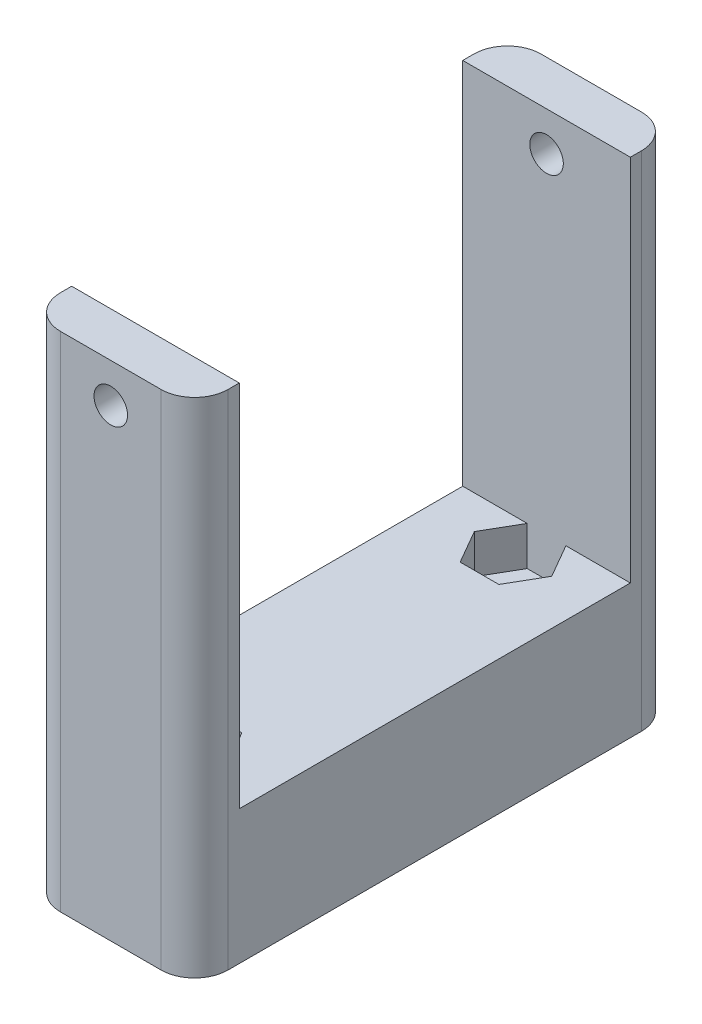
SolidWorks part; units mm, degrees
ref_plane "Alzado" through (0, 0, 0) normal (0, 0, 1) x (1, 0, 0)
ref_plane "Planta" through (0, 0, 0) normal (0, 1, 0) x (1, 0, 0)
ref_plane "Vista lateral" through (0, 0, 0) normal (1, 0, 0) x (0, 0, -1)
sketch "Croquis1" plane through (0, 0, 0) normal (0, 1, 0) x (1, 0, 0)
  line L1 (-7.5, 21.5) -> (7.5, 21.5)
  line L2 (-7.5, 21.5) -> (-7.5, -21.5)
  line L3 (-7.5, -21.5) -> (7.5, -21.5)
  line L4 (7.5, 21.5) -> (7.5, -21.5)
  point P4 (7.5, 0)
  point P6 (0, -21.5)
  dimension "D1" = 43
  dimension "D2" = 15
extrude "Saliente-Extruir1" add sketch "Croquis1" along normal blind 12
sketch "Croquis2" plane through (0, 12, 0) normal (0, 1, 0) x (1, 0, 0)
  line L0 (7.5, -21.5) -> (7.5, 21.5) construction
  line L1 (-7.5, 21.5) -> (7.5, 21.5)
  line L2 (-7.5, 21.5) -> (-7.5, 17.5)
  line L3 (-7.5, 17.5) -> (7.5, 17.5)
  line L4 (7.5, 21.5) -> (7.5, 17.5)
  line L5 (-7.5, 21.5) -> (-7.5, -21.5) construction
  line L6 (7.5, -21.5) -> (-7.5, -21.5)
  line L7 (7.5, -21.5) -> (7.5, -17.5)
  line L8 (7.5, -17.5) -> (-7.5, -17.5)
  line L9 (-7.5, -21.5) -> (-7.5, -17.5)
  dimension "D1" = 4
  dimension "D2" = 4
extrude "Saliente-Extruir2" add sketch "Croquis2" along normal blind 33
sketch "Croquis3" plane through (0, 0, 0) normal (0, -1, 0) x (1, 0, 0)
  line L0 (0, 14.5) -> (0, -14.5) construction
  circle A0 centre (0, 14.5) radius 1.5
  circle A1 centre (0, -14.5) radius 1.5
  point P4 (0, 0)
  dimension "D1" = 3
  dimension "D2" = 3
  dimension "D3" = 26
extrude "Cortar-Extruir1" cut sketch "Croquis3" against normal blind 13
sketch "Croquis4" plane through (0, 12, 0) normal (0, 1, 0) x (1, 0, 0)
  line L1 (3.4641, 14.5) -> (1.7321, 17.5)
  line L2 (1.7321, 17.5) -> (-1.7321, 17.5)
  line L3 (-1.7321, 17.5) -> (-3.4641, 14.5)
  line L4 (-3.4641, 14.5) -> (-1.7321, 11.5)
  line L5 (-1.7321, 11.5) -> (1.7321, 11.5)
  line L6 (1.7321, 11.5) -> (3.4641, 14.5)
  line L7 (3.4641, -14.5) -> (1.7321, -11.5)
  line L8 (1.7321, -11.5) -> (-1.7321, -11.5)
  line L9 (-1.7321, -11.5) -> (-3.4641, -14.5)
  line L10 (-3.4641, -14.5) -> (-1.7321, -17.5)
  line L11 (-1.7321, -17.5) -> (1.7321, -17.5)
  line L12 (1.7321, -17.5) -> (3.4641, -14.5)
  circle A0 centre (0, 14.5) radius 3 construction
  circle A1 centre (0, -14.5) radius 3 construction
  circle A2 centre (0, -14.5) radius 1.5 construction
  point P10 (0, 0)
  dimension "D1" = 6
  dimension "D2" = 6
extrude "Cortar-Extruir2" cut sketch "Croquis4" against normal blind 3.5
fillet "Redondeo1" radius 3 4 edges at (7.5, 22.5, 21.5) (-7.5, 22.5, 21.5) (7.5, 22.5, -21.5) (-7.5, 22.5, -21.5)
sketch "Croquis5" plane through (0, 0, -21.5) normal (0, 0, -1) x (-1, 0, 0)
  line L4 (-4.5, 0) -> (4.5, 0) construction
  circle A0 centre (0, 41.5) radius 1.5
  point P4 (0, 0)
  dimension "D1" = 40
  dimension "D2" = 3
extrude "Cortar-Extruir3" cut sketch "Croquis5" against normal through all both and the other way through all
equation "\"D1@Croquis1\"=35.00+8mm"
